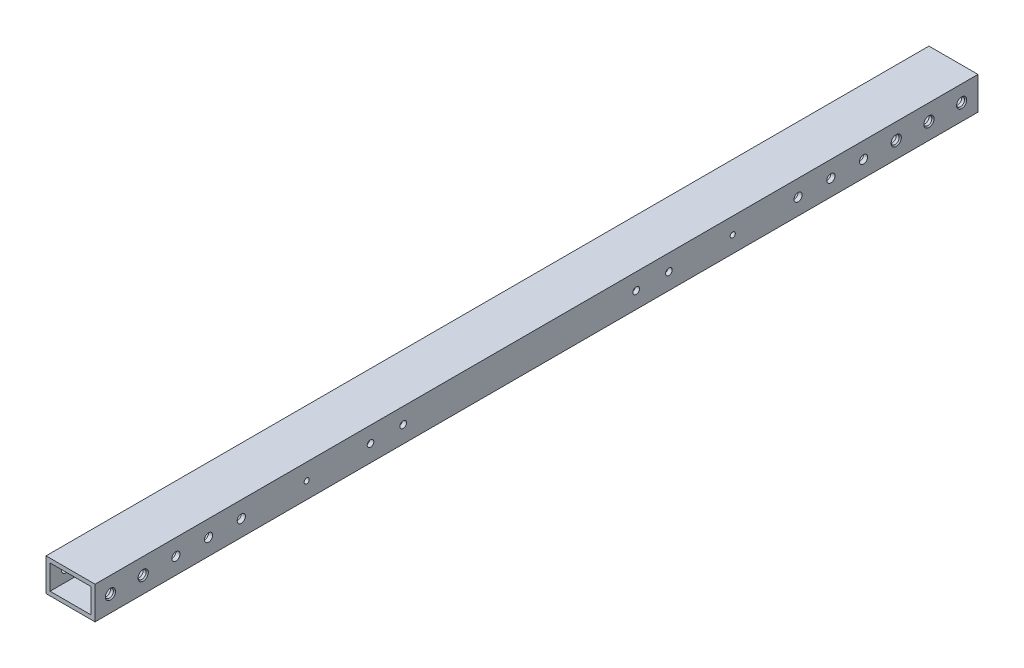
SolidWorks part; units mm, degrees
ref_plane "Front Plane" through (0, 0, 0) normal (0, 0, 1) x (1, 0, 0)
ref_plane "Top Plane" through (0, 0, 0) normal (0, 1, 0) x (1, 0, 0)
ref_plane "Right Plane" through (0, 0, 0) normal (1, 0, 0) x (0, 0, -1)
sketch "Sketch1" plane through (0, 0, 0) normal (0, 0, 1) x (1, 0, 0)
  line L0 (-15.875, 9.525) -> (15.875, 9.525)
  line L2 (-19.05, 12.7) -> (19.05, 12.7)
  line L3 (-19.05, 12.7) -> (-19.05, -12.7)
  line L4 (-19.05, -12.7) -> (19.05, -12.7)
  line L5 (19.05, 12.7) -> (19.05, -12.7)
  line L10 (15.875, 9.525) -> (15.875, -9.525)
  line L11 (-15.875, -9.525) -> (15.875, -9.525)
  line L12 (-15.875, 9.525) -> (-15.875, -9.525)
  point P12 (0, 12.7)
  point P14 (19.05, 0)
  dimension "Wall Thickness" = 3.175
  dimension "Outside Width" = 38.1
  dimension "Outside Height" = 25.4
  dimension "Inside Height" = 19.05
  dimension "Inside Width" = 31.75
sketch "Sketch2" plane through (0, 0, 0) normal (1, 0, 0) x (0, 0, -1)
  line L0 (342.9, 0) -> (-342.9, 0)
  point P4 (0, 0)
  point P7 (-342.9, 0)
  point P10 (342.9, 0)
  dimension "Length" = 685.8
sketch "Sketch3" plane through (0, 0, 0) normal (0, 0, 1) x (1, 0, 0)
  line L21 (19.05, 12.7) -> (-19.05, 12.7)
  line L22 (19.05, -12.7) -> (19.05, 12.7)
  line L23 (-19.05, -12.7) -> (19.05, -12.7)
  line L24 (-19.05, 12.7) -> (-19.05, -12.7)
  line L25 (19.05, 12.7) -> (-19.05, 12.7)
  line L26 (19.05, -12.7) -> (19.05, 12.7)
  line L27 (-19.05, -12.7) -> (19.05, -12.7)
  line L28 (-19.05, 12.7) -> (-19.05, -12.7)
  line L29 (15.875, 9.525) -> (-15.875, 9.525)
  line L30 (15.875, -9.525) -> (15.875, 9.525)
  line L31 (-15.875, -9.525) -> (15.875, -9.525)
  line L32 (-15.875, 9.525) -> (-15.875, -9.525)
  line L33 (15.875, 9.525) -> (-15.875, 9.525)
  line L34 (15.875, -9.525) -> (15.875, 9.525)
  line L35 (-15.875, -9.525) -> (15.875, -9.525)
  line L36 (-15.875, 9.525) -> (-15.875, -9.525)
  dimension "D1" = 0
  dimension "D2" = 0
extrude "Boss-Extrude1" add sketch "Sketch3" along normal up to vertex (342.9 mm away) and the other way up to vertex (342.9 mm away) up to point (0, 0, 342.9) other way up to point (0, 0, -342.9)
sketch "Drawing Reference" plane through (0, 0, 0) normal (1, 0, 0) x (0, 0, -1)
  line L0 (-342.9, 0) -> (342.9, 0) construction
  line L1 (0, -12.7) -> (0, 12.7) construction
  line L2 (-342.9, -12.7) -> (342.9, -12.7) construction
  line L5 (-342.9, 12.7) -> (342.9, 12.7) construction
  point P7 (-315.468, 0)
  point P8 (315.468, 0)
  dimension "D1" = 27.432
sketch "Sketch4" plane through (-19.05, 0, 0) normal (-1, 0, 0) x (0, 0, 1)
  line L0 (-342.9, 0) -> (-330.2, 0)
  line L1 (-342.9, 12.7) -> (-342.9, -12.7) construction
  line L2 (-330.2, 0) -> (-304.8, 0)
  line L3 (-304.8, 0) -> (-279.4, 0)
  line L4 (-279.4, 0) -> (-254, 0)
  line L5 (-254, 0) -> (-228.6, 0)
  line L6 (-228.6, 0) -> (-203.2, 0)
  line L7 (342.9, 0) -> (330.9118, 0)
  line L8 (342.9, 12.7) -> (342.9, -12.7) construction
  line L9 (330.9118, 0) -> (305.5118, 0)
  line L10 (305.5118, 0) -> (280.1118, 0)
  line L11 (280.1118, 0) -> (254.7118, 0)
  line L12 (254.7118, 0) -> (229.3118, 0)
hole_wizard "1/4 (0.25) Diameter Hole2" positions "Sketch7" profile "Sketch8" hole size "1/4" standard "ANSI Inch" end condition through all
sketch "Sketch7" plane through (-19.05, 0, 0) normal (-1, 0, 0) x (0, 0, 1)
  point P0 (-330.2, 0)
  point P3 (-304.8, 0)
  point P7 (330.9118, 0)
  point P11 (-279.4, 0)
  point P14 (305.5118, 0)
sketch "Sketch8" plane through (-19.05, 0, -330.2) normal (0, 1, 0) x (0, 0, 1)
  line L0 (0, 0) -> (0, 38.1)
  line L1 (0, 38.1) -> (3.9624, 38.1)
  line L2 (3.175, 37.1942) -> (3.175, 0)
  line L5 (3.175, 0) -> (0, 0)
  line L7 (3.9624, 38.1) -> (3.175, 37.1942)
  line L8 (-3.9624, 38.1) -> (-3.175, 37.1942) construction
  line L11 (0, -6.35) -> (0, 107.95) construction
  dimension "Thru Hole Dia." = 6.35
  dimension "Thru Hole Depth" = 38.1
  dimension "Far C'Sink Dia." = 7.9248
  dimension "Far C'Sink Angle" = 82
hole_wizard "1/4 (0.25) Diameter Hole3" positions "Sketch9" profile "Sketch10" hole size "1/4" standard "ANSI Inch" end condition through all
sketch "Sketch9" plane through (19.05, 0, 0) normal (1, 0, 0) x (0, 0, -1)
  point P0 (-280.1118, 0)
  point P3 (-254.7118, 0)
  point P6 (-229.3118, 0)
  point P9 (254, 0)
  point P12 (228.6, 0)
  point P15 (203.2, 0)
sketch "Sketch10" plane through (19.05, 0, 280.1118) normal (0, 1, 0) x (0, 0, -1)
  line L0 (0, 0) -> (0, 38.1)
  line L1 (0, 38.1) -> (3.175, 38.1)
  line L2 (3.175, 38.1) -> (3.175, 0)
  line L5 (3.175, 0) -> (0, 0)
  line L11 (0, -6.35) -> (0, 107.95) construction
  dimension "Thru Hole Dia." = 6.35
  dimension "Thru Hole Depth" = 38.1
hole_wizard "5/32 (0.15625) Diameter Hole1" positions "Sketch11" profile "Sketch12" hole size "5/32" standard "ANSI Inch" end condition through all
sketch "Sketch11" plane through (19.05, 0, 0) normal (1, 0, 0) x (0, 0, -1)
  point P0 (152.4, 0)
  point P3 (-178.5118, 0)
sketch "Sketch12" plane through (19.05, 0, -152.4) normal (0, 1, 0) x (0, 0, -1)
  line L0 (0, 0) -> (0, 38.1)
  line L1 (0, 38.1) -> (1.9844, 38.1)
  line L2 (1.9844, 38.1) -> (1.9844, 0)
  line L5 (1.9844, 0) -> (0, 0)
  line L11 (0, -6.35) -> (0, 107.95) construction
  dimension "Thru Hole Dia." = 3.9688
  dimension "Thru Hole Depth" = 38.1
sketch "Sketch13" plane through (19.05, 0, 0) normal (1, 0, 0) x (0, 0, -1)
  line L0 (-103.5434, 0.3445) -> (-128.9434, 0.3445)
  line L1 (77.4316, -0.0006) -> (102.8316, -0.0006)
hole_wizard "#10 Clearance Hole1" positions "Sketch14" profile "Sketch15" hole size "#10" standard "ANSI Inch" end condition through all
sketch "Sketch14" plane through (19.05, 0, 0) normal (1, 0, 0) x (0, 0, -1)
  point P0 (-128.9434, 0.3445)
  point P3 (-103.5434, 0.3445)
  point P7 (77.4316, -0.0006)
  point P10 (102.8316, -0.0006)
sketch "Sketch15" plane through (19.05, 0.3445, 128.9434) normal (0, 1, 0) x (0, 0, -1)
  line L0 (0, 0) -> (0, 38.1)
  line L1 (0, 38.1) -> (2.5527, 38.1)
  line L2 (2.5527, 38.1) -> (2.5527, 0)
  line L5 (2.5527, 0) -> (0, 0)
  line L11 (0, -6.35) -> (0, 107.95) construction
  dimension "Thru Hole Dia." = 5.1054
  dimension "Thru Hole Depth" = 38.1
equation "\"D1@Drawing Reference\"=\"Outside Width@Sketch1\" * 0.72"
